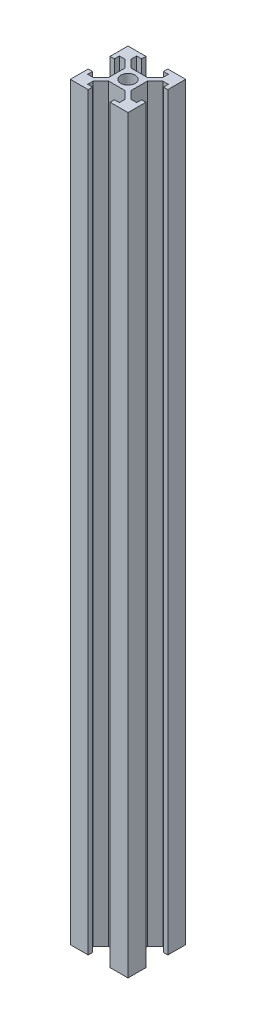
SolidWorks part; units mm, degrees
material "7075-T6 (SN)"
ref_plane "前视基准面" through (0, 0, 0) normal (0, 0, 1) x (1, 0, 0)
ref_plane "上视基准面" through (0, 0, 0) normal (0, 1, 0) x (1, 0, 0)
ref_plane "右视基准面" through (0, 0, 0) normal (1, 0, 0) x (0, 0, -1)
sketch "草图1" plane through (0, 0, 0) normal (0, 1, 0) x (1, 0, 0)
  line L0 (-6.5607, 5.5) -> (-3.9, 2.8393)
  line L1 (-10, 10) -> (10, 10)
  line L2 (-10, 10) -> (-10, -10)
  line L3 (-10, -10) -> (10, -10)
  line L4 (10, 10) -> (10, -10)
  line L5 (-10, 10) -> (10, -10) construction
  line L6 (-10, -10) -> (10, 10) construction
  line L7 (-3.9, 3.9) -> (3.9, 3.9)
  line L8 (-3.9, 3.9) -> (-3.9, -3.9)
  line L9 (-3.9, -3.9) -> (3.9, -3.9)
  line L10 (3.9, 3.9) -> (3.9, -3.9)
  line L11 (-3.9, 3.9) -> (3.9, -3.9) construction
  line L12 (-3.9, -3.9) -> (3.9, 3.9) construction
  line L13 (-10, 10) -> (-5.5, 10)
  line L14 (-10, 10) -> (-10, 5.5)
  line L15 (-10, 5.5) -> (-5.5, 5.5)
  line L16 (-5.5, 10) -> (-5.5, 5.5)
  line L17 (-10, 5.5) -> (-8.5, 5.5)
  line L18 (-10, 5.5) -> (-10, 3.8)
  line L19 (-10, 3.8) -> (-8.5, 3.8)
  line L20 (-8.5, 5.5) -> (-8.5, 3.8)
  line L21 (-5.5, 6.5607) -> (-2.8393, 3.9)
  line L22 (-3.8, 10) -> (-3.8, 8.5)
  line L23 (-5.5, 8.5) -> (-3.8, 8.5)
  line L24 (0, 10) -> (0, -10) construction
  line L25 (5.5, 8.5) -> (3.8, 8.5)
  line L26 (3.8, 10) -> (3.8, 8.5)
  line L27 (5.5, 6.5607) -> (2.8393, 3.9)
  line L28 (6.5607, 5.5) -> (3.9, 2.8393)
  line L29 (10, 3.8) -> (8.5, 3.8)
  line L30 (8.5, 5.5) -> (8.5, 3.8)
  line L31 (10, 5.5) -> (8.5, 5.5)
  line L32 (10, 5.5) -> (10, 3.8)
  line L33 (10, 5.5) -> (5.5, 5.5)
  line L34 (5.5, 10) -> (5.5, 5.5)
  line L35 (10, 10) -> (5.5, 10)
  line L36 (10, 10) -> (10, 5.5)
  line L37 (-10, 0) -> (10, 0) construction
  line L38 (-10, -3.8) -> (-8.5, -3.8)
  line L39 (-8.5, -5.5) -> (-8.5, -3.8)
  line L40 (-10, -5.5) -> (-5.5, -5.5)
  line L41 (-6.5607, -5.5) -> (-3.9, -2.8393)
  line L42 (-5.5, -6.5607) -> (-2.8393, -3.9)
  line L43 (-5.5, -10) -> (-5.5, -5.5)
  line L44 (-5.5, -8.5) -> (-3.8, -8.5)
  line L45 (-3.8, -10) -> (-3.8, -8.5)
  line L46 (3.8, -10) -> (3.8, -8.5)
  line L47 (6.5607, -5.5) -> (3.9, -2.8393)
  line L48 (5.5, -6.5607) -> (2.8393, -3.9)
  line L49 (-10, 10) -> (10, 10)
  line L50 (-10, -10) -> (10, -10)
  line L51 (5.5, -8.5) -> (3.8, -8.5)
  line L52 (5.5, -10) -> (5.5, -5.5)
  line L53 (10, -5.5) -> (5.5, -5.5)
  line L54 (10, -3.8) -> (8.5, -3.8)
  line L55 (8.5, -5.5) -> (8.5, -3.8)
  circle A0 centre (0, 0) radius 2.5
  dimension "D1" = 5
  dimension "D2" = 20
  dimension "D3" = 20
  dimension "D4" = 7.8
  dimension "D5" = 4.5
  dimension "D6" = 1.7
  dimension "D7" = 0.75
  dimension "D8" = 1.5
extrude "凸台-拉伸1" add sketch "草图1" along normal blind 260 contours L1 L34 L33 L31 L4 | L4 L31 L30 L29 | L34 L27 L7 L10 L28 L33 | L34 L1 L26 L25 | L10 L7 L8 L9 A0 | L16 L23 L22 L1 | L16 L1 L2 L15 | L20 L15 L2 L19 | L21 L16 L15 L0 L8 L7 | L3 L43 L40 L2 | L3 L45 L44 L43 | L2 L40 L39 L38 | L43 L42 L9 L8 L41 L40 | L53 L47 L10 L9 L48 L52 | L4 L53 L52 L50 | L55 L53 L4 L54 | L3 L52 L51 L46
